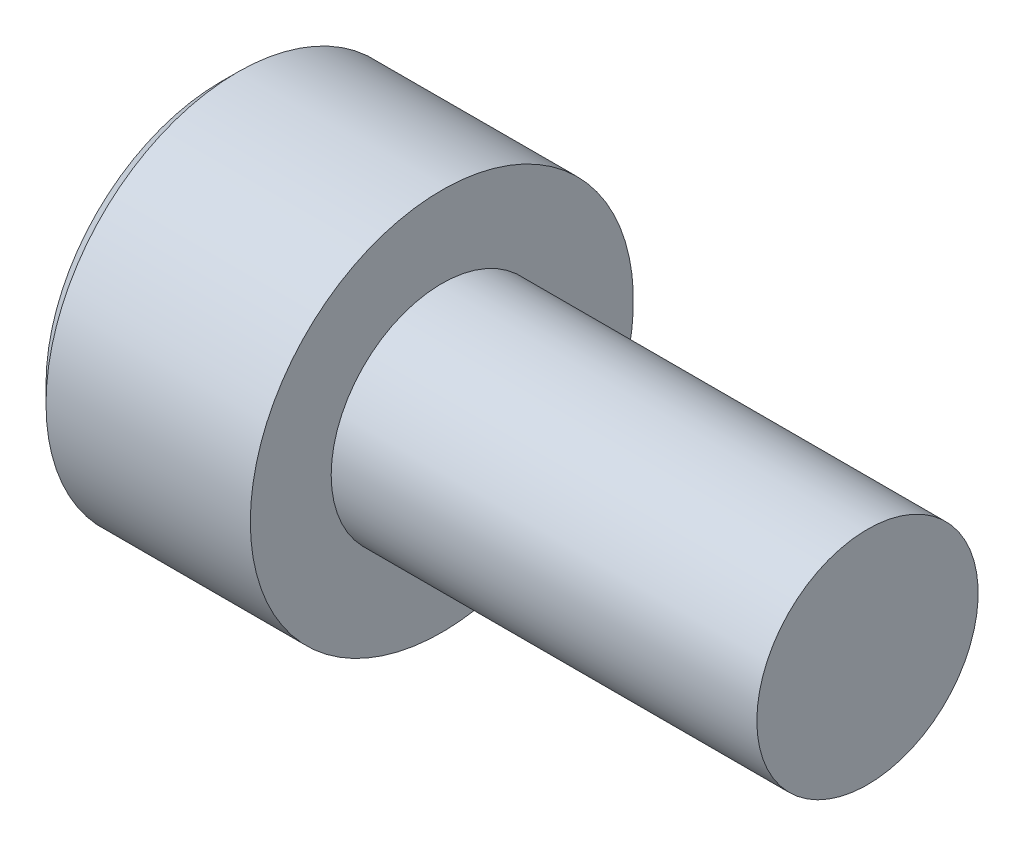
SolidWorks part; units mm, degrees
material "SCM435"
ref_plane "Front Plane" through (0, 0, 0) normal (0, 0, 1) x (1, 0, 0)
ref_plane "Top Plane" through (0, 0, 0) normal (0, 1, 0) x (1, 0, 0)
ref_plane "Right Plane" through (0, 0, 0) normal (1, 0, 0) x (0, 0, -1)
sketch "Sketch1" plane through (0, 0, 0) normal (0, 0, 1) x (1, 0, 0)
  line L2 (-2.6, 0) -> (5, 0)
  line L3 (5, 0) -> (5, 1.3)
  line L4 (5, 1.3) -> (0, 1.3)
  line L5 (0, 1.3) -> (0, 2.25)
  line L6 (0, 2.25) -> (-2.6, 2.25)
  line L7 (-2.6, 2.25) -> (-2.6, 0)
  line L8 (-2.6, 0) -> (5, 0) construction
  line L9 (0, 0) -> (0, 2.25) construction
  dimension "E" = 2.6
  dimension "L" = 5
  dimension "A" = 4.5
  dimension "M" = 2.6
revolve "Revolve1" add sketch "Sketch1" about L8
cosmetic thread "Thread1" parameters "L_s"=5, "ATD"=2.1129
chamfer "Chamfer1" distance 0.2 1 edges at (-2.6, 0, 2.25)
sketch "Sketch2" plane through (0, 0, 0) normal (0, 0, 1) x (1, 0, 0)
  line L0 (-0.8991, 0) -> (-1.5, 1)
  line L1 (-2.6, 0) -> (5, 0) construction
  line L2 (-1.5, 1) -> (-2.6, 1)
  line L3 (-2.6, 2.25) -> (-2.6, 0) construction
  line L4 (-2.6, 1) -> (-2.6, 0)
  line L5 (-2.6, 0) -> (-0.8991, 0) construction
  line L6 (-0.8991, 0) -> (-2.6, 0)
  dimension "FIX_3" = 59
revolve "Cut-Revolve1" cut sketch "Sketch2" about L5
sketch "Sketch3" plane through (-2.6, 0, 0) normal (-1, 0, 0) x (0, 0, 1)
  line L0 (0, -1.1547) -> (0, 1.1547) construction
  line L1 (0, -1.1547) -> (1, -0.5774)
  line L2 (1, -0.5774) -> (1, 0.5774)
  line L3 (1, 0.5774) -> (0, 1.1547)
  line L4 (0, 1.1547) -> (-1, 0.5774)
  line L5 (-1, 0.5774) -> (-1, -0.5774)
  line L6 (-1, -0.5774) -> (0, -1.1547)
  line L7 (-1, 0) -> (1, 0) construction
  circle A0 centre (0, 0) radius 1 construction
extrude "Cut-Extrude1" cut sketch "Sketch3" against normal blind 1.1
